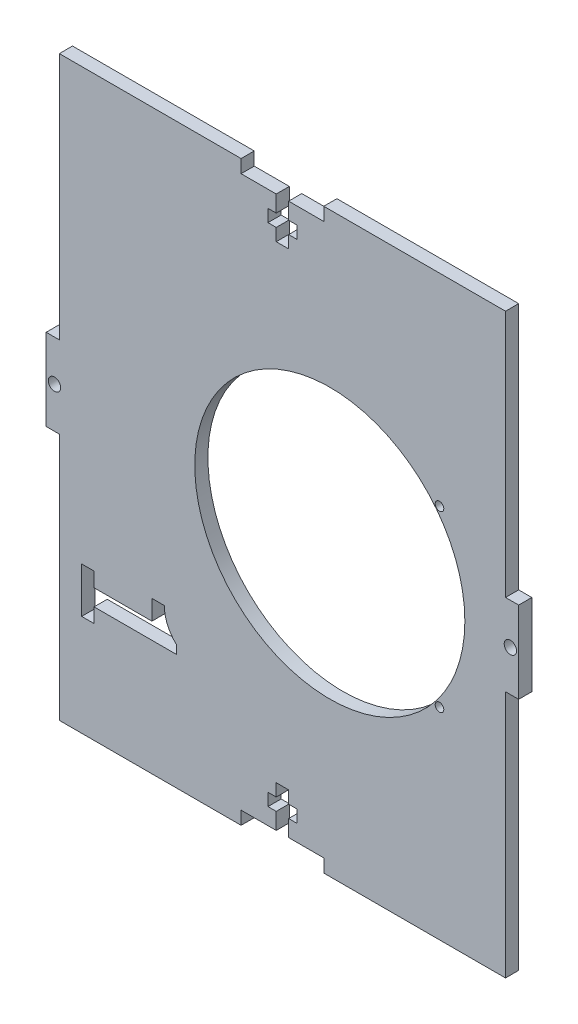
SolidWorks part; units mm, degrees
ref_plane "Front Plane" through (0, 0, 0) normal (0, 0, 1) x (1, 0, 0)
ref_plane "Top Plane" through (0, 0, 0) normal (0, 1, 0) x (1, 0, 0)
ref_plane "Right Plane" through (0, 0, 0) normal (1, 0, 0) x (0, 0, -1)
sketch "Sketch1" plane through (0, 0, 0) normal (0, 0, 1) x (1, 0, 0)
  line L1 (-57.15, 69.85) -> (57.15, 69.85)
  line L2 (-57.15, 69.85) -> (-57.15, -69.85)
  line L3 (-57.15, -69.85) -> (57.15, -69.85)
  line L4 (57.15, 69.85) -> (57.15, -69.85)
  line L5 (-57.15, 69.85) -> (57.15, -69.85) construction
  line L6 (-57.15, -69.85) -> (57.15, 69.85) construction
  point P0 (0, 0)
  dimension "D1" = 139.7
  dimension "D2" = 114.3
extrude "Boss-Extrude1" add sketch "Sketch1" along normal blind 3.18
sketch "Sketch2" plane through (0, 0, 3.18) normal (0, 0, 1) x (1, 0, 0)
  line L0 (0, 0) -> (57.15, 0) construction
  line L1 (-10, 69.85) -> (10, 69.85)
  line L2 (-10, 69.85) -> (-10, 66.67)
  line L3 (-10, 66.67) -> (-1.5, 66.67)
  line L4 (10, 69.85) -> (10, 66.67)
  line L5 (57.15, -69.85) -> (57.15, 69.85) construction
  line L6 (0, 0) -> (0, 69.85) construction
  line L7 (-1.5, 56.67) -> (1.5, 56.67)
  line L8 (-1.5, 56.67) -> (-1.5, 59.67)
  line L10 (1.5, 56.67) -> (1.5, 59.67)
  line L12 (57.15, 69.85) -> (-57.15, 69.85) construction
  line L13 (3.5, 62.67) -> (1.5, 62.67)
  line L14 (3.5, 62.67) -> (3.5, 59.67)
  line L15 (3.5, 59.67) -> (1.5, 59.67)
  line L16 (-3.5, 62.67) -> (-3.5, 59.67)
  line L17 (-10, -69.85) -> (-10, -66.67)
  line L18 (-10, -66.67) -> (-1.5, -66.67)
  line L19 (-1.5, -62.67) -> (-1.5, -66.67)
  line L20 (-1.5, -62.67) -> (-3.5, -62.67)
  line L21 (-3.5, -62.67) -> (-3.5, -59.67)
  line L22 (1.5, 66.67) -> (10, 66.67)
  line L23 (-1.5, 62.67) -> (-3.5, 62.67)
  line L24 (-1.5, -59.67) -> (-3.5, -59.67)
  line L25 (-1.5, -56.67) -> (-1.5, -59.67)
  line L26 (-1.5, -56.67) -> (1.5, -56.67)
  line L27 (-1.5, 59.67) -> (-3.5, 59.67)
  line L28 (1.5, -56.67) -> (1.5, -59.67)
  line L29 (-1.5, 62.67) -> (-1.5, 66.67)
  line L30 (1.5, 62.67) -> (1.5, 66.67)
  line L31 (3.5, -59.67) -> (1.5, -59.67)
  line L32 (3.5, -62.67) -> (3.5, -59.67)
  line L33 (3.5, -62.67) -> (1.5, -62.67)
  line L34 (1.5, -62.67) -> (1.5, -66.67)
  line L35 (1.5, -66.67) -> (10, -66.67)
  line L36 (10, -69.85) -> (10, -66.67)
  line L37 (-10, -69.85) -> (10, -69.85)
  line L38 (-57.15, 69.85) -> (-57.15, -69.85) construction
  line L39 (-57.15, 69.85) -> (-53.97, 69.85)
  line L40 (-57.15, 69.85) -> (-57.15, 9.875)
  line L41 (-57.15, 9.875) -> (-53.97, 9.875)
  line L42 (-53.97, 69.85) -> (-53.97, 9.875)
  line L43 (-57.15, -69.85) -> (-53.97, -69.85)
  line L44 (-57.15, -69.85) -> (-57.15, -9.875)
  line L45 (-57.15, -9.875) -> (-53.97, -9.875)
  line L46 (-53.97, -69.85) -> (-53.97, -9.875)
  line L47 (57.15, -9.875) -> (53.97, -9.875)
  line L48 (53.97, -69.85) -> (53.97, -9.875)
  line L49 (57.15, -69.85) -> (53.97, -69.85)
  line L50 (57.15, -69.85) -> (57.15, -9.875)
  line L51 (57.15, 9.875) -> (53.97, 9.875)
  line L52 (53.97, 69.85) -> (53.97, 9.875)
  line L53 (57.15, 69.85) -> (53.97, 69.85)
  line L54 (57.15, 69.85) -> (57.15, 9.875)
  circle A0 centre (-55.15, 0) radius 1.5
  circle A1 centre (55.15, 0) radius 1.5
  point P0 (0, 50.5662)
  point P5 (0, 32.0079)
  point P10 (15.4931, 34.4893)
  dimension "D11" = 3
  dimension "D12" = 2
  dimension "D1" = 20
  dimension "D2" = 19.75
  dimension "D3" = 4
  dimension "D4" = 3
  dimension "D5" = 3.18
  dimension "D6" = 7
  dimension "D7" = 3
  dimension "D8" = 3
  dimension "D9" = 3.18
  dimension "D10" = 3.18
extrude "Cut-Extrude1" cut sketch "Sketch2" against normal through all
sketch "Sketch4" plane through (0, 0, 0) normal (0, 0, 1) x (1, 0, 0)
  line L3 (-25.5711, -41.8625) -> (-45.5711, -41.8625)
  line L4 (-45.5711, -41.8625) -> (-45.5711, -45.3625)
  line L5 (-45.5711, -45.3625) -> (-48.5711, -45.3625)
  line L6 (-48.5711, -45.3625) -> (-48.5711, -34.3625)
  line L7 (-48.5711, -34.3625) -> (-45.5711, -34.3625)
  line L8 (-45.5711, -34.3625) -> (-45.5711, -37.8625)
  line L9 (-45.5711, -37.8625) -> (-31.5711, -37.8625)
  line L10 (-31.5711, -37.8625) -> (-31.5711, -33.0876)
  line L11 (-31.5711, -33.0876) -> (-28.5711, -33.0876)
  line L12 (-25.5711, -39.8625) -> (-25.5711, -41.8625)
  arc A0 (-28.5711, -33.0876) -> (-25.5711, -39.8625) centre (-19.4212, -33.0876) ccw
  point P18 (-27.1302, -35.8044)
  point P19 (-24.8898, -42.49)
  point P20 (-25.5711, -39.8625)
  dimension "D1" = 11
  dimension "D2" = 4
  dimension "D3" = 3
  dimension "D4" = 3
  dimension "D5" = 14
  dimension "D6" = 20
  dimension "D7" = 3
extrude "Cut-Extrude5" cut sketch "Sketch4" along normal blind 12
sketch "Sketch5" plane through (0, 0, 3.18) normal (0, 0, 1) x (1, 0, 0)
  circle A0 centre (11.4626, 0) radius 32.6714
  point P2 (11.4626, 0)
extrude "Cut-Extrude6" cut sketch "Sketch5" against normal blind 10
sketch "Sketch9" plane through (0, 0, 3.18) normal (0, 0, 1) x (1, 0, 0)
  circle A0 centre (37.9914, -21.1) radius 1.042
  circle A1 centre (37.9914, 21.0083) radius 1.042
  point P5 (37.9914, 21.0083)
extrude "Cut-Extrude8" cut sketch "Sketch9" against normal through all
